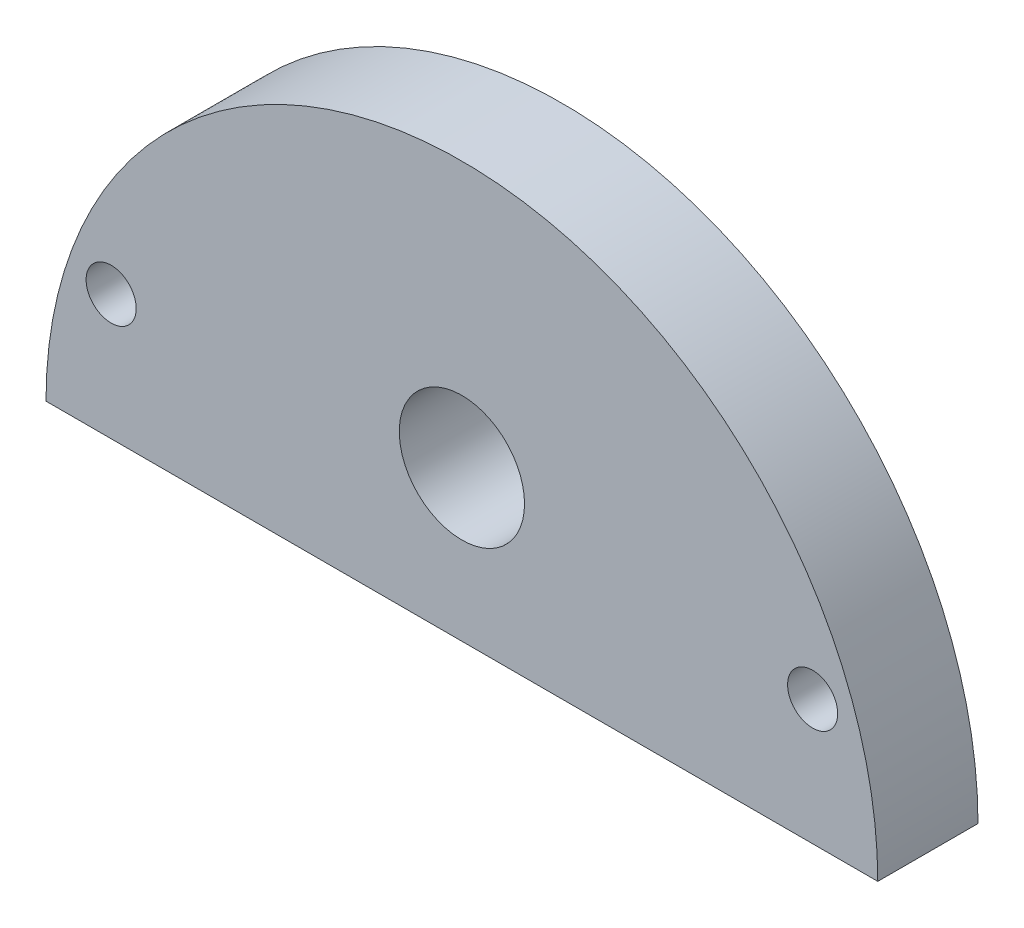
SolidWorks part; units mm, degrees
ref_plane "前视基准面" through (0, 0, 0) normal (0, 0, 1) x (1, 0, 0)
ref_plane "上视基准面" through (0, 0, 0) normal (0, 1, 0) x (1, 0, 0)
ref_plane "右视基准面" through (0, 0, 0) normal (1, 0, 0) x (0, 0, -1)
sketch "草图1" plane through (0, 0, 0) normal (0, 0, 1) x (1, 0, 0)
  line L0 (-33.2014, 0) -> (33.2014, 0)
  arc A0 (33.2014, 0) -> (-33.2014, 0) centre (0, 0) ccw
  circle A1 centre (0, 12) radius 5
  dimension "D1" = 10
  dimension "D2" = 12
extrude "凸台-拉伸1" add sketch "草图1" along normal blind 8
sketch "草图2" plane through (0, 0, 8) normal (0, 0, 1) x (1, 0, 0)
  line L0 (-33.2014, 0) -> (33.2014, 0) construction
  circle A0 centre (-28, 10) radius 2
  circle A1 centre (0, 12) radius 5 construction
  circle A2 centre (28, 10) radius 2
  dimension "D1" = 10
  dimension "D2" = 28
  dimension "D3" = 10
  dimension "D4" = 28
extrude "切除-拉伸1" cut sketch "草图2" against normal blind 8
